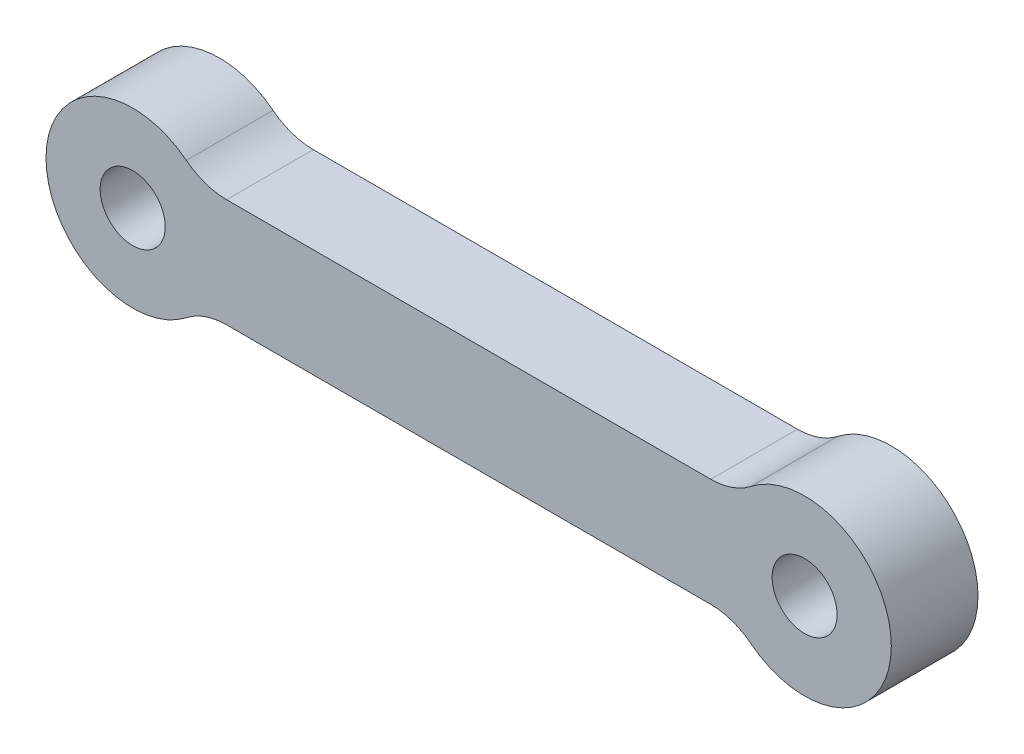
SolidWorks part; units mm, degrees
ref_plane "Front Plane" through (0, 0, 0) normal (0, 0, 1) x (1, 0, 0)
ref_plane "Top Plane" through (0, 0, 0) normal (0, 1, 0) x (1, 0, 0)
ref_plane "Right Plane" through (0, 0, 0) normal (1, 0, 0) x (0, 0, -1)
sketch "Sketch1" plane through (0, 0, 0) normal (0, 0, 1) x (1, 0, 0)
  line L0 (-15.5, 0) -> (15.5, 0) construction
  line L1 (0, 0) -> (0, 5.2529) construction
  line L3 (-11.1699, 2.5) -> (11.1699, 2.5)
  line L5 (-11.1699, -2.5) -> (11.1699, -2.5)
  line L7 (-12.3775, 2.5) -> (12.3775, -2.5) construction
  line L8 (-12.3775, -2.5) -> (12.3775, 2.5) construction
  arc A0 (-13.0256, 3.1429) -> (-13.0256, -3.1429) centre (-15.5, 0) ccw
  circle A1 centre (-15.5, 0) radius 1.5
  circle A2 centre (15.5, 0) radius 1.5
  arc A3 (13.0256, 3.1429) -> (13.0256, -3.1429) centre (15.5, 0) cw
  arc A4 (11.1699, -2.5) -> (13.0256, -3.1429) centre (11.1699, -5.5) cw
  arc A5 (11.1699, 2.5) -> (13.0256, 3.1429) centre (11.1699, 5.5) ccw
  arc A6 (-13.0256, -3.1429) -> (-11.1699, -2.5) centre (-11.1699, -5.5) cw
  arc A7 (-11.1699, 2.5) -> (-13.0256, 3.1429) centre (-11.1699, 5.5) cw
  point P4 (0, 0)
  dimension "D2" = 8
  dimension "D3" = 3
  dimension "D5" = 3
  dimension "D1" = 31
  dimension "D4" = 5
extrude "Boss-Extrude1" add sketch "Sketch1" along normal blind 4
